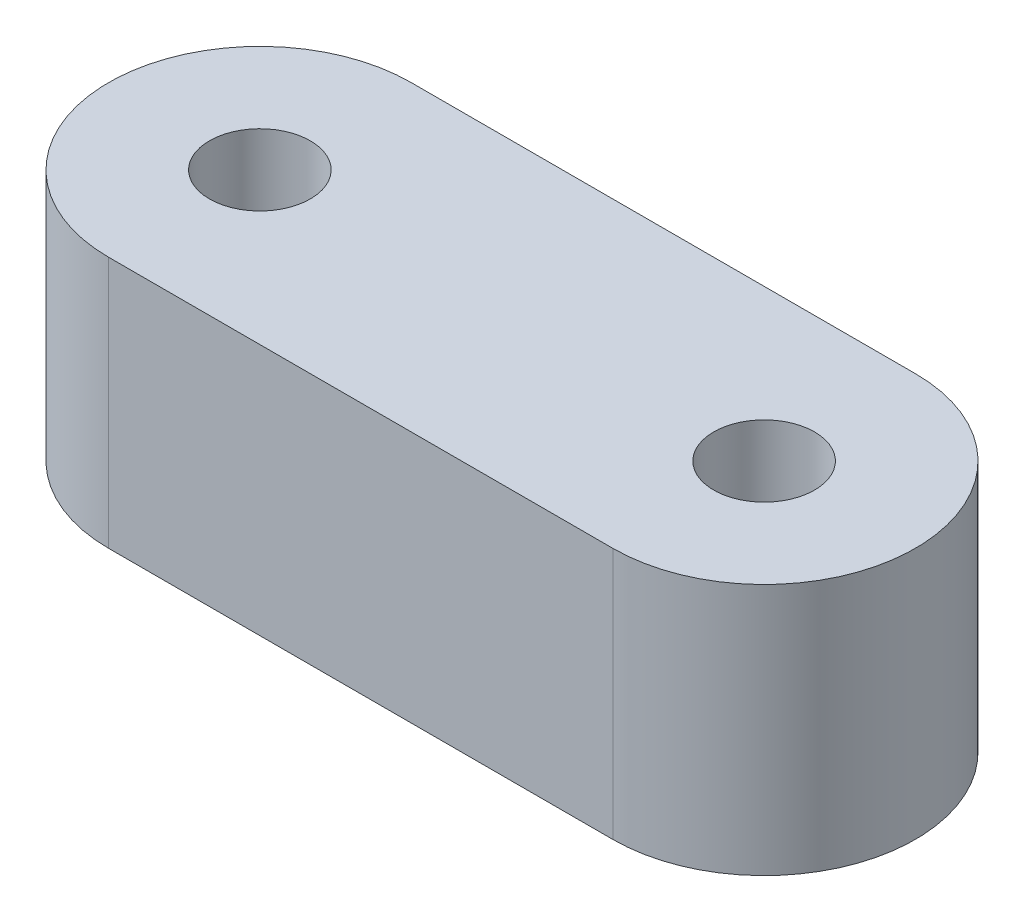
SolidWorks part; units mm, degrees
ref_plane "Front Plane" through (0, 0, 0) normal (0, 0, 1) x (1, 0, 0)
ref_plane "Top Plane" through (0, 0, 0) normal (0, 1, 0) x (1, 0, 0)
ref_plane "Right Plane" through (0, 0, 0) normal (1, 0, 0) x (0, 0, -1)
sketch "Sketch3" plane through (0, 0, 0) normal (0, 1, 0) x (1, 0, 0)
  line L0 (-63.5, 0) -> (-38.1, 0) construction
  line L1 (-6.985, 0) -> (6.985, 0) construction
  line L2 (-63.5, 7.62) -> (-38.1, 7.62)
  line L3 (-63.5, -7.62) -> (-38.1, -7.62)
  arc A0 (-63.5, 7.62) -> (-63.5, -7.62) centre (-63.5, 0) ccw
  arc A1 (-38.1, -7.62) -> (-38.1, 7.62) centre (-38.1, 0) ccw
  point P5 (-50.8, 0)
  dimension "D2" = 7.62
  dimension "D1" = 25.4
  dimension "D3" = 63.5
extrude "Boss-Extrude1" add sketch "Sketch3" along normal blind 12.7
sketch "Sketch4" plane through (0, 12.7, 0) normal (0, 1, 0) x (1, 0, 0)
  circle A0 centre (-63.5, 0) radius 2.54
  circle A1 centre (-38.1, 0) radius 2.54
  dimension "D1" = 5.08
extrude "Cut-Extrude3" cut sketch "Sketch4" against normal through all
equation "\"TibiaLength\"= 5in"
equation "\"TibiaRadius\"= 0.3in"
equation "\"TibiaDistFromCentre\"= \"TibiaLength\" / 2"
equation "\"TibiaThickness\"= 0.5in"
equation "\"HoleRadius\"= 0.2in"
equation "\"D1@Sketch3\"= \"TibiaLength\" * 0.2"
equation "\"D2@Sketch3\"= \"TibiaRadius\""
equation "\"D3@Sketch3\"= \"TibiaDistFromCentre\""
equation "\"D1@Boss-Extrude1\"= \"TibiaThickness\""
equation "\"D1@Sketch4\"= \"HoleRadius\""
